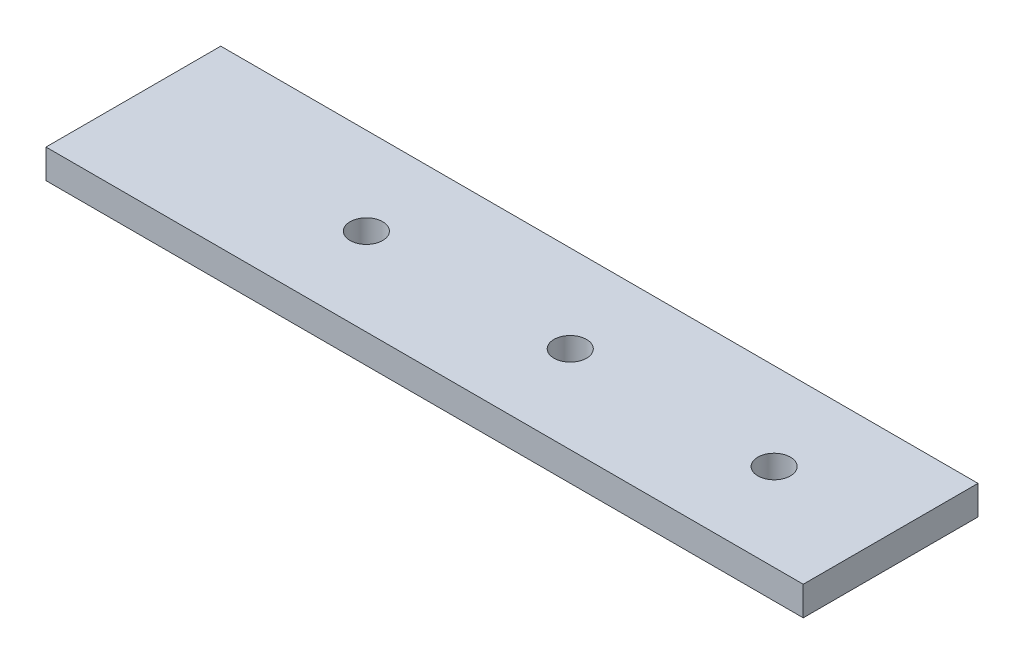
SolidWorks part; units mm, degrees
ref_plane "Front" through (0, 0, 0) normal (0, 0, 1) x (1, 0, 0)
ref_plane "Top" through (0, 0, 0) normal (0, 1, 0) x (1, 0, 0)
ref_plane "Right" through (0, 0, 0) normal (1, 0, 0) x (0, 0, -1)
sketch "Sketch1" plane through (0, 0, 0) normal (0, 1, 0) x (1, 0, 0)
  line L1 (0, 0) -> (65, 0)
  line L2 (0, 0) -> (0, 15)
  line L3 (0, 15) -> (65, 15)
  line L4 (65, 0) -> (65, 15)
  circle A0 centre (55, 7.5) radius 1.4
  circle A1 centre (37.5, 7.5) radius 1.4
  circle A2 centre (20, 7.5) radius 1.4
  dimension "D6" = 45
  dimension "D7" = 2.8
  dimension "D8" = 2.8
  dimension "D9" = 2.8
  dimension "D1" = 65
  dimension "D2" = 15
  dimension "D3" = 7.5
  dimension "D4" = 10
  dimension "D5" = 27.5
extrude "Boss-Extrude1" add sketch "Sketch1" along normal blind 2.5
